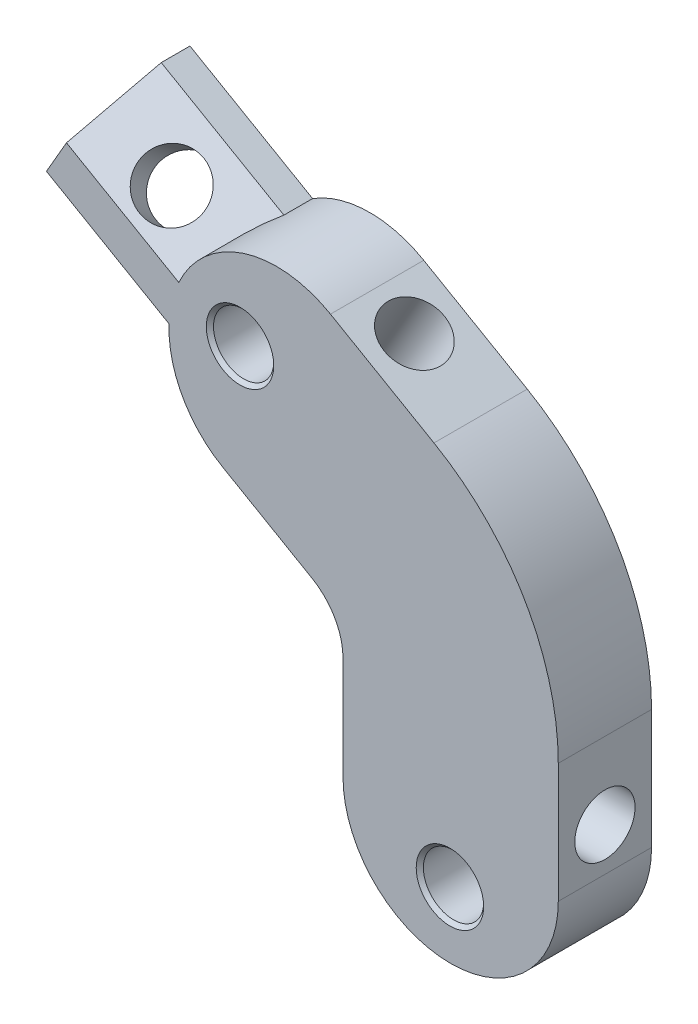
SolidWorks part; units mm, degrees
material "ABS"
ref_plane "Front Plane" through (0, 0, 0) normal (0, 0, 1) x (1, 0, 0)
ref_plane "Top Plane" through (0, 0, 0) normal (0, 1, 0) x (1, 0, 0)
ref_plane "Right Plane" through (0, 0, 0) normal (1, 0, 0) x (0, 0, -1)
ref_plane "Plane4" through (0, 0, 0) normal (0, 0, -1) x (-1, 0, 0)
sketch "Sketch1" plane through (0, 0, 0) normal (0, 0, -1) x (-1, 0, 0)
  line L0 (37.2391, 21.5) -> (52.8275, 30.5) construction
  line L1 (-15, -11.3397) -> (-15, -28)
  line L2 (52.8275, 30.5) -> (56.3275, 24.4378)
  line L3 (56.3275, 24.4378) -> (39.2378, 14.5711)
  line L4 (52.8275, 30.5) -> (49.3275, 36.5622)
  line L5 (15, -28) -> (15, -13.6603)
  line L6 (49.3275, 36.5622) -> (32.2378, 26.6954)
  line L7 (19.3301, -6.1603) -> (31.7487, 1.0096)
  line L11 (16.7487, 26.9904) -> (2.3205, 18.6603)
  arc A0 (15, -13.6603) -> (19.3301, -6.1603) centre (23.6603, -13.6603) cw
  arc A1 (2.3205, 18.6603) -> (-15, -11.3397) centre (19.641, -11.3397) ccw
  arc A2 (-15, -28) -> (15, -28) centre (0, -28) ccw
  arc A3 (31.7487, 1.0096) -> (39.2487, 14) centre (24.2487, 14) ccw
  arc A4 (31.7487, 26.9904) -> (16.7487, 26.9904) centre (24.2487, 14) ccw
  arc A5 (39.2487, 14) -> (39.2378, 14.5711) centre (24.2487, 14) ccw
  arc A6 (32.2378, 26.6954) -> (31.7487, 26.9904) centre (24.2487, 14) ccw
  dimension "D3" = 30
  dimension "D1" = 30
  dimension "D2" = 30
  dimension "D4" = 18
  dimension "D5" = 7
  dimension "D6" = 7
extrude "Boss-Extrude1" add sketch "Sketch1" against normal blind 13
sketch "Sketch2" plane through (-7.5, -12.9904, 0) normal (-0.5, -0.866, 0) x (0.866, -0.5, 0)
  line L1 (-28, 0) -> (-11.3397, 0) construction
  arc A0 (-25.0212, 9.4176) -> (-18.9788, 9.4176) centre (-22, 6.5) ccw
  arc A1 (-18.9788, 9.4176) -> (-25.0212, 9.4176) centre (-22, 6.5) ccw
  dimension "D2" = 4.2
  dimension "D1" = 6.5
extrude "Cut-Extrude1" cut sketch "Sketch2" against normal through all
sketch "Sketch3" plane through (-15, 0, 0) normal (-1, 0, 0) x (0, 0, 1)
  line L0 (0, -11.3397) -> (0, -28) construction
  arc A0 (9.4176, -18.9788) -> (9.4176, -25.0212) centre (6.5, -22) ccw
  arc A1 (9.4176, -25.0212) -> (9.4176, -18.9788) centre (6.5, -22) ccw
  dimension "D1" = 6.5
extrude "Cut-Extrude2" cut sketch "Sketch3" against normal through all
hole_wizard "Ø8.4 (8.4) Diameter Hole1" positions "Sketch5" profile "Sketch4" hole size "Ø8.4" standard "ANSI Metric" end condition through all
sketch "Sketch5" plane through (0, 0, 0) normal (0, 0, -1) x (-1, 0, 0)
  line L0 (16.1603, -9.3301) -> (-10.359, 5.9808)
  arc A0 (19.3301, -6.1603) -> (15, -13.6603) centre (23.6603, -13.6603) ccw construction
  arc A1 (2.3205, 18.6603) -> (-15, -11.3397) centre (19.641, -11.3397) ccw construction
  point P0 (29.3474, 16.8312)
  point P1 (0.0974, -33.8312)
  dimension "D1" = 29.25
  dimension "D2" = 29.25
sketch "Sketch4" plane through (-29.3474, 16.8312, 0) normal (1, 0, 0) x (0, 1, 0)
  line L0 (0, 0) -> (0, 13)
  line L1 (0, 13) -> (4.2, 13)
  line L2 (4.2, 13) -> (4.2, 0)
  line L5 (4.2, 0) -> (0, 0)
  line L11 (0, -6.35) -> (0, 107.95) construction
  dimension "Thru Hole Dia." = 8.4
  dimension "Thru Hole Depth" = 13
sketch "Sketch6" plane through (247.7942, -143.0641, 0) normal (-0.866, 0.5, 0) x (0, 0, 1)
  line L0 (28.5, -0.0974) -> (-45.6564, -0.0974)
  line L1 (6.5, 359.2487) -> (6.5, -7.3026)
  line L2 (-279.5, -39.2487) -> (-279.5, 380.0834)
  line L3 (28.5, 320.0974) -> (-338.6796, 320.0974)
  line L4 (-279.5, 320.0974) -> (6.5, -0.0974) construction
  line L5 (2.7473, 4.1039) -> (15.1496, 15.1817)
  line L6 (2.7473, 4.1039) -> (-8.9438, -6.3386)
  line L7 (-8.9438, -6.3386) -> (-18.8712, 5.0428)
  line L8 (-18.8712, 5.0428) -> (11.6127, 23.4624)
  line L9 (11.6127, 23.4624) -> (15.1496, 15.1817)
  dimension "D1" = 48.229
chamfer "Chamfer2" distance 9 angle 43.06 1 edges at (-40.7827, 31.6288, 0)
chamfer "Chamfer3" distance 8 angle 46.94 1 edges at (-47.7827, 19.5044, 13)
sketch "Sketch11" plane through (-0.3764, -0.6519, 0.7035) normal (0.3653, 0.6328, -0.6828) x (-0.9308, 0.2544, -0.2623)
  line L0 (57.2798, 20.9987) -> (40.4176, 14.5134) construction
  circle A0 centre (45.8311, 22.4561) radius 4.2
  dimension "D1" = 5.47
  dimension "D2" = 8.4
extrude "Cut-Extrude5" cut sketch "Sketch11" against normal blind 10
chamfer "Chamfer4" distance 0.5 angle 45 4 edges at (-29.3474, 21.0312, 0) (-0.0974, -29.6312, 0) (-0.0974, -29.6312, 13) (-29.3474, 21.0312, 13)
mirror "Mirror1" about plane through (0, 0, 0) normal (0, 0, -1) of bodies 110
sketch "Sketch12" plane through (0, 0, 0) normal (0, 0, -1) x (-1, 0, 0)
  line L1 (462.4416, -68.2786) -> (-431.3929, -68.2786)
  line L2 (462.4416, -68.2786) -> (462.4416, 66.4442)
  line L3 (462.4416, 66.4442) -> (-431.3929, 66.4442)
  line L4 (-431.3929, -68.2786) -> (-431.3929, 66.4442)
extrude "Cut-Extrude6" cut sketch "Sketch12" against normal through all
